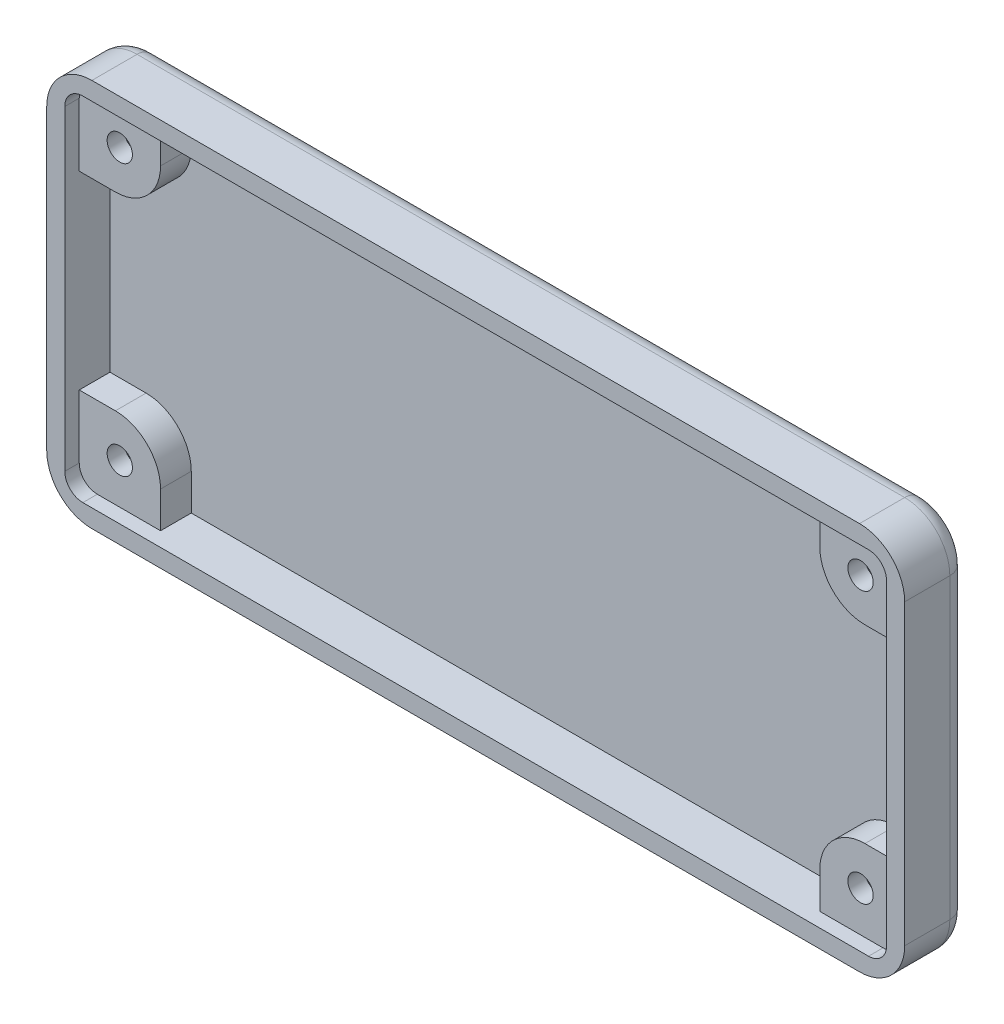
SolidWorks part; units mm, degrees
ref_plane "前视基准面" through (0, 0, 0) normal (0, 0, 1) x (1, 0, 0)
ref_plane "上视基准面" through (0, 0, 0) normal (0, 1, 0) x (1, 0, 0)
ref_plane "右视基准面" through (0, 0, 0) normal (1, 0, 0) x (0, 0, -1)
other "Configuration Table"
sketch "草图1" plane through (0, 0, 1.6001) normal (0, 0, -1) x (-1, 0, 0)
  line L1 (-92.4875, 2.4873) -> (2.4873, 2.4873)
  line L2 (-92.4875, 2.4873) -> (-92.4875, -40.4874)
  line L3 (-92.4875, -40.4874) -> (2.4873, -40.4874)
  line L4 (2.4873, 2.4873) -> (2.4873, -40.4874)
  line L5 (-90.4875, 0.4873) -> (0.4873, 0.4873)
  line L6 (-90.4875, 0.4873) -> (-90.4875, -38.4874)
  line L7 (-90.4875, -38.4874) -> (0.4873, -38.4874)
  line L8 (0.4873, 0.4873) -> (0.4873, -38.4874)
  point P12 (0, 0)
  point P13 (0, 0)
  point P14 (0, 0)
  point P15 (0, 0)
extrude "凸台-拉伸1" add sketch "草图1" along normal blind 5
sketch "草图2" plane through (0, 0, -3.3999) normal (0, 0, -1) x (-1, 0, 0)
  line L1 (-90.4875, 0.4873) -> (-81.4875, 0.4873)
  line L2 (-90.4875, 0.4873) -> (-90.4875, -8.5127)
  line L3 (-90.4875, -8.5127) -> (-81.4875, -8.5127)
  line L4 (-81.4875, 0.4873) -> (-81.4875, -8.5127)
  line L5 (0.4873, 0.4873) -> (-8.5127, 0.4873)
  line L6 (0.4873, 0.4873) -> (0.4873, -8.5127)
  line L7 (0.4873, -8.5127) -> (-8.5127, -8.5127)
  line L8 (-8.5127, 0.4873) -> (-8.5127, -8.5127)
  line L9 (0.4873, -38.4874) -> (-8.5127, -38.4874)
  line L10 (0.4873, -38.4874) -> (0.4873, -29.4874)
  line L11 (0.4873, -29.4874) -> (-8.5127, -29.4874)
  line L12 (-8.5127, -38.4874) -> (-8.5127, -29.4874)
  line L13 (-90.4875, -38.4874) -> (-81.4875, -38.4874)
  line L14 (-90.4875, -38.4874) -> (-90.4875, -29.4874)
  line L15 (-90.4875, -29.4874) -> (-81.4875, -29.4874)
  line L16 (-81.4875, -38.4874) -> (-81.4875, -29.4874)
  dimension "D1" = 9
  dimension "D2" = 9
  dimension "D3" = 9
  dimension "D4" = 9
  dimension "D5" = 9
  dimension "D6" = 9
  dimension "D7" = 9
  dimension "D8" = 9
extrude "凸台-拉伸2" add sketch "草图2" against normal blind 3.4
fillet "圆角1" radius 5 4 edges at (8.5127, -29.4874, -1.6999) (81.4875, -29.4874, -1.6999) (8.5127, -8.5127, -1.6999) (81.4875, -8.5127, -1.6999)
sketch "草图3" plane through (0, 0, -3.3999) normal (0, 0, -1) x (-1, 0, 0)
  line L1 (-92.4875, 2.4873) -> (2.4873, 2.4873)
  line L2 (-92.4875, 2.4873) -> (-92.4875, -40.4874)
  line L3 (-92.4875, -40.4874) -> (2.4873, -40.4874)
  line L4 (2.4873, 2.4873) -> (2.4873, -40.4874)
extrude "凸台-拉伸3" add sketch "草图3" along normal blind 2
sketch "草图4" plane through (0, 0, -5.3999) normal (0, 0, -1) x (-1, 0, 0)
  circle A0 centre (-86.0002, -4) radius 2.4
  circle A1 centre (-4, -4) radius 2.4
  circle A2 centre (-4, -34.0001) radius 2.4
  circle A3 centre (-86.0002, -34.0001) radius 2.4
extrude "切除-拉伸1" cut sketch "草图4" against normal blind 3.5
sketch "草图5" plane through (0, 0, -1.8999) normal (0, 0, -1) x (-1, 0, 0)
  circle A0 centre (-86.0002, -4) radius 1.4
  circle A1 centre (-4, -4) radius 1.4
  circle A2 centre (-4, -34.0001) radius 1.4
  circle A3 centre (-86.0002, -34.0001) radius 1.4
extrude "切除-拉伸2" cut sketch "草图5" against normal through all
fillet "圆角2" radius 5 4 edges at (92.4875, -40.4874, -1.8999) (-2.4873, -40.4874, -1.8999) (-2.4873, 2.4873, -1.8999) (92.4875, 2.4873, -1.8999)
fillet "圆角3" radius 2 8 edges at (91.023, -39.0229, -5.3999) (92.4875, -19, -5.3999) (91.023, 1.0228, -5.3999) (45.0001, 2.4873, -5.3999) (-1.0228, 1.0228, -5.3999) (-2.4873, -19, -5.3999) (-1.0228, -39.0229, -5.3999) (45.0001, -40.4874, -5.3999)
fillet "圆角4" radius 2 4 edges at (90.4875, -38.4874, 0.8001) (90.4875, 0.4873, 0.8001) (-0.4873, 0.4873, 0.8001) (-0.4873, -38.4874, 0.8001)
